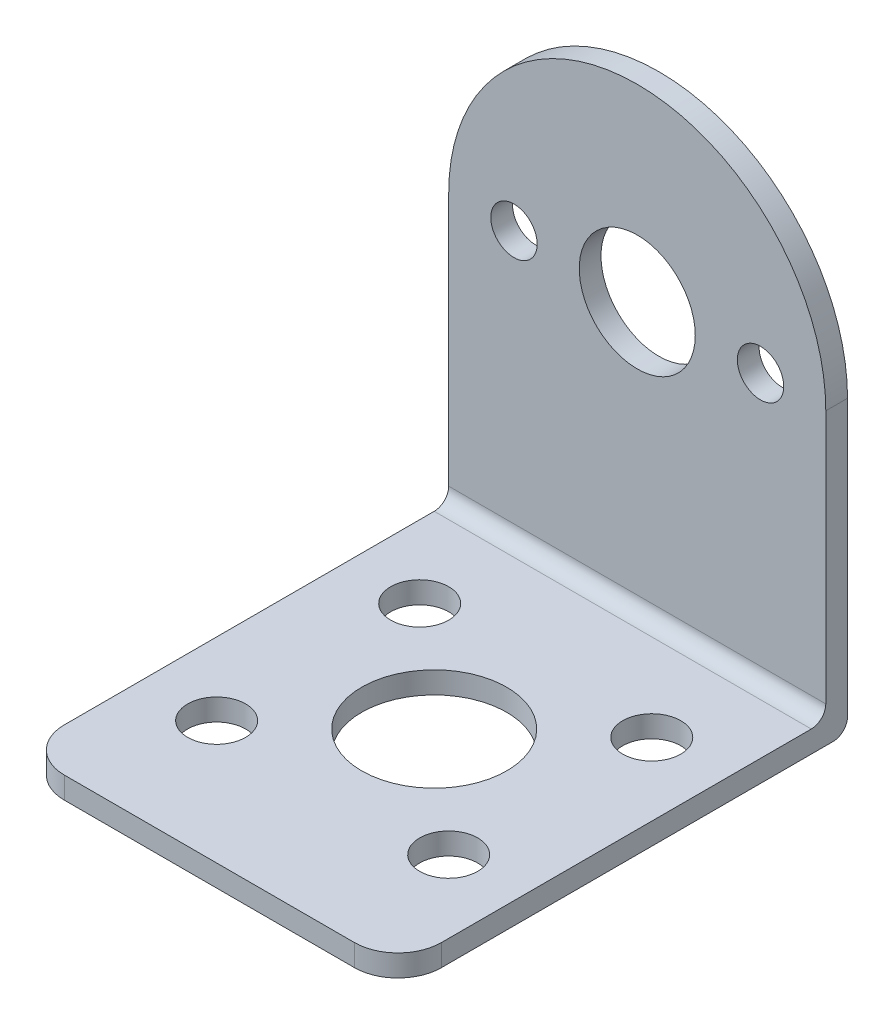
SolidWorks part; units mm, degrees
material "1060 Alloy"
ref_plane "Front Plane" through (0, 0, 0) normal (0, 0, 1) x (1, 0, 0)
ref_plane "Top Plane" through (0, 0, 0) normal (0, 1, 0) x (1, 0, 0)
ref_plane "Right Plane" through (0, 0, 0) normal (1, 0, 0) x (0, 0, -1)
sketch "Sketch1" plane through (0, 0, 0) normal (0, 1, 0) x (1, 0, 0)
  line L1 (-13, -15.5) -> (13, -15.5)
  line L2 (-13, -15.5) -> (-13, 15.5)
  line L3 (-13, 15.5) -> (13, 15.5)
  line L4 (13, -15.5) -> (13, 15.5)
  line L5 (-13, -15.5) -> (13, 15.5) construction
  line L6 (-13, 15.5) -> (13, -15.5) construction
  line L11 (-8, -7) -> (8, 7) construction
  line L12 (-6.4948, 5.683) -> (8, -7) construction
  circle A0 centre (0, 0) radius 5
  circle A1 centre (-8, 7) radius 2
  circle A2 centre (8, 7) radius 2
  circle A3 centre (-8, -7) radius 2
  circle A4 centre (8, -7) radius 2
  point P0 (0, 0)
  dimension "D3" = 10
  dimension "D6" = 4
  dimension "D7" = 4
  dimension "D8" = 4
  dimension "D9" = 4
  dimension "D1" = 31
  dimension "D2" = 26
  dimension "D4" = 16
  dimension "D5" = 14
extrude "Boss-Extrude1" add sketch "Sketch1" along normal blind 1.5
sketch "Sketch2" plane through (0, 1.5, 0) normal (0, 1, 0) x (1, 0, 0)
  line L0 (13, -15.5) -> (13, 15.5) construction
  line L1 (-13, 15.5) -> (13, 15.5)
  line L2 (-13, 15.5) -> (-13, 14)
  line L3 (-13, 14) -> (13, 14)
  line L4 (13, 15.5) -> (13, 14)
  dimension "D1" = 1.5
extrude "Boss-Extrude2" add sketch "Sketch2" along normal blind 31.5
sketch "Sketch3" plane through (0, 0, -14) normal (0, 0, 1) x (1, 0, 0)
  line L0 (0, 33) -> (0, 7) construction
  line L1 (-13, 33) -> (13, 33) construction
  line L4 (-13, 20) -> (-13, 33)
  line L5 (-13, 33) -> (13, 33)
  line L6 (13, 20) -> (13, 33)
  line L7 (-2.8284, 17.1716) -> (13, 33) construction
  line L8 (-13, 33) -> (2.8284, 17.1716) construction
  arc A0 (13, 20) -> (-13, 20) centre (0, 20) ccw
  circle A1 centre (0, 20) radius 4
  circle A2 centre (8.5, 20) radius 1.6
  circle A3 centre (-8.5, 20) radius 1.6
  line M10 (13, 1.5) -> (13, 33)
  line M11 (13, 33) -> (-13, 33)
  line M12 (-13, 33) -> (-13, 1.5)
  dimension "D2" = 8
  dimension "D3" = 3.2
  dimension "D1" = 26
  dimension "D4" = 8.5
extrude "Cut-Extrude1" cut sketch "Sketch3" against normal blind 1.5 contours A0 L5 M12 | A0 M10 M11 | A3 | A1 | A2
fillet "Fillet1" radius 1 2 edges at (0, 0, -15.5) (0, 1.5, -14)
fillet "Fillet2" radius 3 2 edges at (13, 0.75, 15.5) (-13, 0.75, 15.5)
